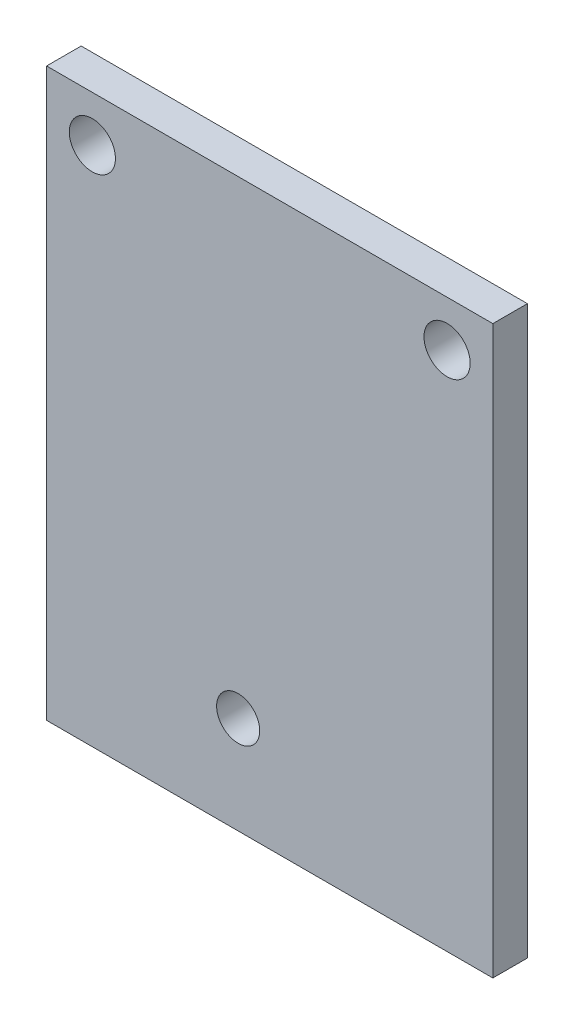
SolidWorks part; units mm, degrees
ref_plane "Front Plane" through (0, 0, 0) normal (0, 0, 1) x (1, 0, 0)
ref_plane "Top Plane" through (0, 0, 0) normal (0, 1, 0) x (1, 0, 0)
ref_plane "Right Plane" through (0, 0, 0) normal (1, 0, 0) x (0, 0, -1)
sketch "Sketch1" plane through (0, 0, 0) normal (0, 0, 1) x (1, 0, 0)
  line L0 (3, 3) -> (3, -3) construction
  line L1 (3, -3) -> (-3, -3) construction
  line L2 (-3, -3) -> (-3, 3) construction
  line L3 (-3, 3) -> (3, 3) construction
  line L4 (3, 3) -> (3, -3) construction
  line L5 (3, -3) -> (-3, -3) construction
  line L6 (-3, -3) -> (-3, 3) construction
  line L7 (-3, 3) -> (3, 3) construction
  line L9 (-10.25, 10.55) -> (9.75, 10.55)
  line L10 (-10.25, 10.55) -> (-10.25, -14.85)
  line L11 (-10.25, -14.85) -> (9.75, -14.85)
  line L12 (9.75, 10.55) -> (9.75, -14.85)
  dimension "D1" = 20
  dimension "D2" = 25.4
  dimension "D3" = 6.75
  dimension "D4" = 7.55
extrude "Boss-Extrude1" add sketch "Sketch1" along normal blind 1.5494
sketch "Sketch2" plane through (0, 0, 0) normal (0, 0, -1) x (-1, 0, 0)
  line L0 (-9.75, 10.55) -> (10.25, 10.55) construction
  line L1 (-9.75, -14.85) -> (-9.75, 10.55) construction
  line L2 (10.25, 10.55) -> (10.25, -14.85) construction
  line L3 (10.25, 10.55) -> (10.25, -14.85) construction
  circle A2 centre (8.199, 8.4989) radius 1.035
  circle A3 centre (-7.699, 8.4989) radius 1.035
  circle A4 centre (1.6648, -10.4812) radius 0.9652
  dimension "D1" = 2.0701
  dimension "D2" = 2.0511
  dimension "D3" = 2.0511
  dimension "D4" = 2.0511
  dimension "D5" = 1.9304
  dimension "D6" = 8.5852
  dimension "D7" = 21.0312
extrude "Cut-Extrude1" cut sketch "Sketch2" against normal through all
